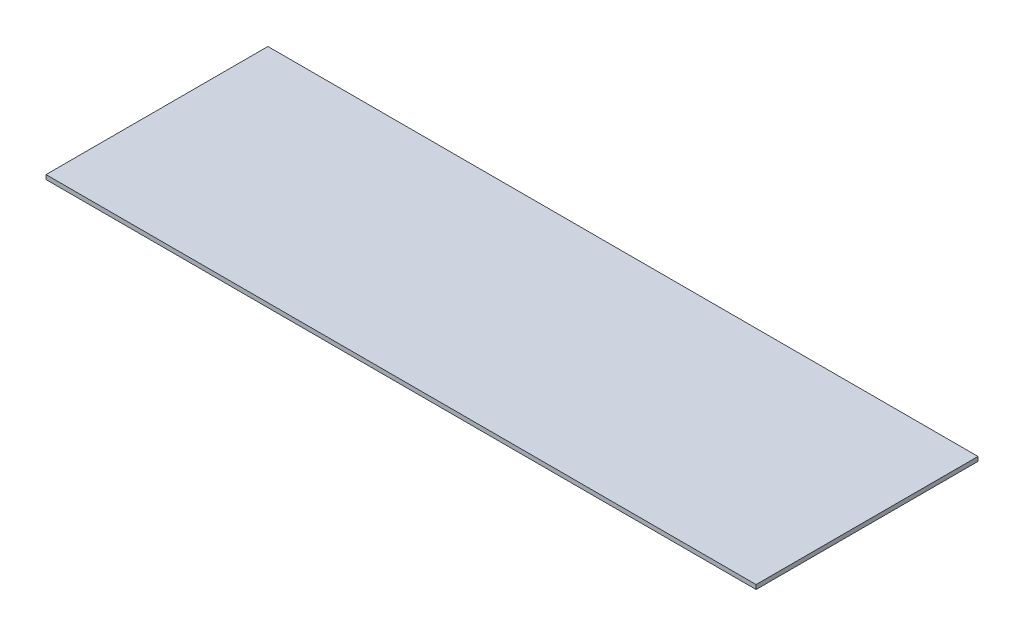
SolidWorks part; units mm, degrees
material "Pine"
ref_plane "Front Plane" through (0, 0, 0) normal (0, 0, 1) x (1, 0, 0)
ref_plane "Top Plane" through (0, 0, 0) normal (0, 1, 0) x (1, 0, 0)
ref_plane "Right Plane" through (0, 0, 0) normal (1, 0, 0) x (0, 0, -1)
sketch "Sketch1" plane through (0, 0, 0) normal (0, 1, 0) x (1, 0, 0)
  line L1 (-522.224, 163.195) -> (522.224, 163.195)
  line L2 (-522.224, 163.195) -> (-522.224, -163.195)
  line L3 (-522.224, -163.195) -> (522.224, -163.195)
  line L4 (522.224, 163.195) -> (522.224, -163.195)
  line L5 (-522.224, 163.195) -> (522.224, -163.195) construction
  line L6 (-522.224, -163.195) -> (522.224, 163.195) construction
  point P0 (0, 0)
  dimension "D1" = 1044.448
extrude "Boss-Extrude1" add sketch "Sketch1" along normal blind 6.35
